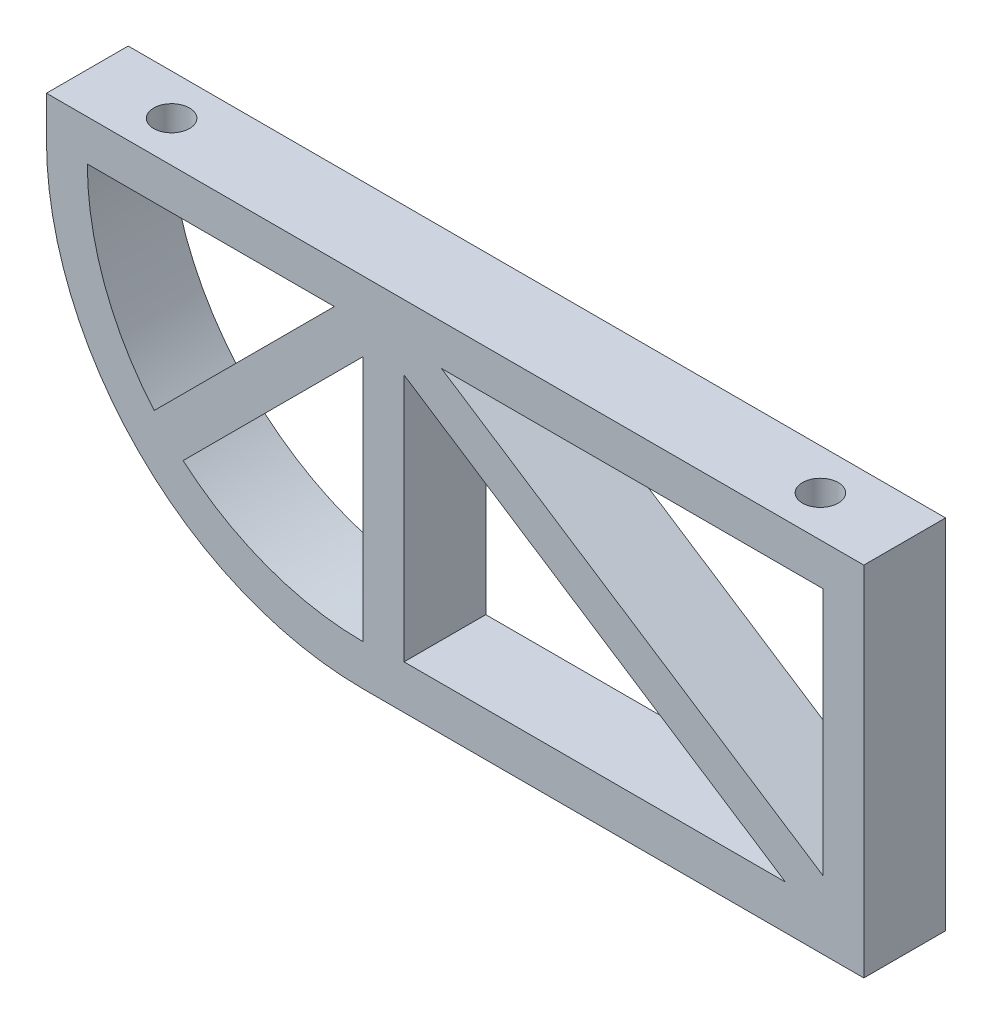
SolidWorks part; units mm, degrees
ref_plane "Alzado" through (0, 0, 0) normal (0, 0, 1) x (1, 0, 0)
ref_plane "Planta" through (0, 0, 0) normal (0, 1, 0) x (1, 0, 0)
ref_plane "Vista lateral" through (0, 0, 0) normal (1, 0, 0) x (0, 0, -1)
sketch "Croquis1" plane through (0, 0, 0) normal (0, 0, 1) x (1, 0, 0)
  line L0 (-26.1016, 12.6074) -> (4.8984, 12.6074) construction
  line L1 (-26.1016, 16.6074) -> (53.8984, 16.6074)
  line L2 (-26.1016, 16.6074) -> (-26.1016, 12.6074)
  line L3 (-26.1016, 12.6074) -> (53.8984, 12.6074)
  line L4 (53.8984, 16.6074) -> (53.8984, 12.6074)
  line L5 (-26.1016, 12.6074) -> (-22.1016, 12.6074) construction
  line L6 (4.8984, 12.6074) -> (53.8984, 12.6074)
  line L7 (4.8984, 12.6074) -> (4.8984, -18.3926)
  line L8 (4.8984, -18.3926) -> (53.8984, -18.3926)
  line L9 (53.8984, 12.6074) -> (53.8984, -18.3926)
  line L10 (53.8984, 12.6074) -> (49.8984, 12.6074) construction
  line L11 (4.8984, -18.3926) -> (8.8984, -18.3926) construction
  line L12 (8.8984, 12.6074) -> (49.8984, -14.0947)
  line L13 (49.8984, 12.6074) -> (8.8984, 12.6074)
  line L26 (49.8984, 12.6074) -> (49.8984, -14.0947)
  line L27 (49.8984, -14.0947) -> (8.8984, -14.0947)
  line L28 (8.8984, 12.6074) -> (8.8984, -14.0947)
  line L32 (7.807, 10.9315) -> (48.807, -15.7706)
  line L33 (9.9899, 14.2833) -> (50.9899, -12.4187)
  line L34 (9.9899, 14.2833) -> (7.807, 10.9315)
  line L36 (50.9899, -12.4187) -> (48.807, -15.7706)
  line L38 (-22.1016, 12.6074) -> (4.8984, -14.3926) construction
  line L39 (4.8984, 12.6074) -> (-14.1934, -6.4845)
  line L40 (3.4842, 14.0216) -> (-15.6077, -5.0703)
  line L41 (6.3127, 11.1932) -> (-12.7792, -7.8987)
  line L42 (-15.6077, -5.0703) -> (-12.7792, -7.8987)
  line L43 (3.4842, 14.0216) -> (6.3127, 11.1932)
  circle A0 centre (4.8984, 12.6074) radius 31
  circle A1 centre (4.8984, 12.6074) radius 27
  dimension "D1" = 4
  dimension "D2" = 80
  dimension "D3" = 31
  dimension "D4" = 4
  dimension "D5" = 4
  dimension "D6" = 4
  dimension "D9" = 2
  dimension "D10" = 2
  dimension "D11" = 2
  dimension "D12" = 2
extrude "Saliente-Extruir1" add sketch "Croquis1" along normal blind 8
sketch "Croquis2" plane through (0, 16.6074, 0) normal (0, 1, 0) x (1, 0, 0)
  line L0 (-26.1016, -8) -> (53.8984, -8) construction
  line L1 (-26.1016, 0) -> (53.8984, 0)
  line L2 (-26.1016, 0) -> (-26.1016, -8)
  line L3 (-26.1016, -8) -> (53.8984, -8)
  line L4 (53.8984, 0) -> (53.8984, -8)
  line L5 (-26.1016, -4) -> (53.8984, -4) construction
  line L6 (13.8984, -8) -> (13.8984, 0) construction
  line L7 (13.8984, -4) -> (45.6484, -4) construction
  line L8 (13.8984, -4) -> (-17.8516, -4) construction
  circle A0 centre (-17.8516, -4) radius 1.75
  circle A1 centre (45.6484, -4) radius 1.75
  dimension "D1" = 31.75
  dimension "D2" = 31.75
extrude "Cortar-Extruir1" cut sketch "Croquis2" against normal blind 8 contours A0 | A1
